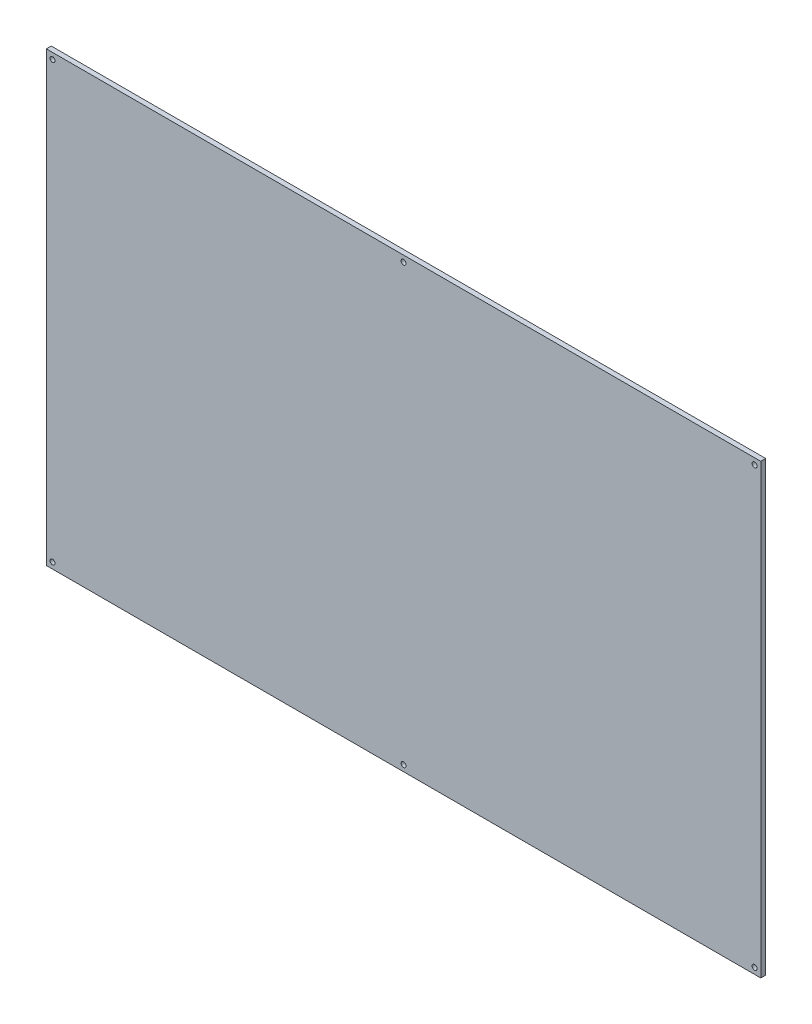
SolidWorks part; units mm, degrees
ref_plane "Plan de face" through (0, 0, 0) normal (0, 0, 1) x (1, 0, 0)
ref_plane "Plan de dessus" through (0, 0, 0) normal (0, 1, 0) x (1, 0, 0)
ref_plane "Plan de droite" through (0, 0, 0) normal (1, 0, 0) x (0, 0, -1)
sketch "Esquisse1" plane through (0, 0, 0) normal (0, 0, 1) x (1, 0, 0)
  line L1 (-46.8817, 28.5715) -> (243.5483, 28.5715)
  line L2 (-46.8817, 28.5715) -> (-46.8817, -153.3285)
  line L3 (-46.8817, -153.3285) -> (243.5483, -153.3285)
  line L4 (243.5483, 28.5715) -> (243.5483, -153.3285)
  circle A0 centre (-44.3817, 26.0715) radius 1
  circle A1 centre (98.3283, 26.0715) radius 1
  circle A2 centre (241.0483, 26.0715) radius 1
  circle A3 centre (241.0483, -150.8285) radius 1
  circle A4 centre (98.3283, -150.8285) radius 1
  circle A5 centre (-44.3817, -150.8285) radius 1
  dimension "D3" = 2.5
  dimension "D1" = 290.43
  dimension "D2" = 181.9
  dimension "D4" = 2.5
  dimension "D5" = 2.5
  dimension "D6" = 2.5
  dimension "D7" = 2.5
  dimension "D8" = 2.5
  dimension "D9" = 2.5
  dimension "D10" = 2.5
  dimension "D11" = 2.5
  dimension "D12" = 2.5
  dimension "D13" = 145.21
  dimension "D14" = 145.21
extrude "Boss.-Extru.1" add sketch "Esquisse1" along normal blind 2
